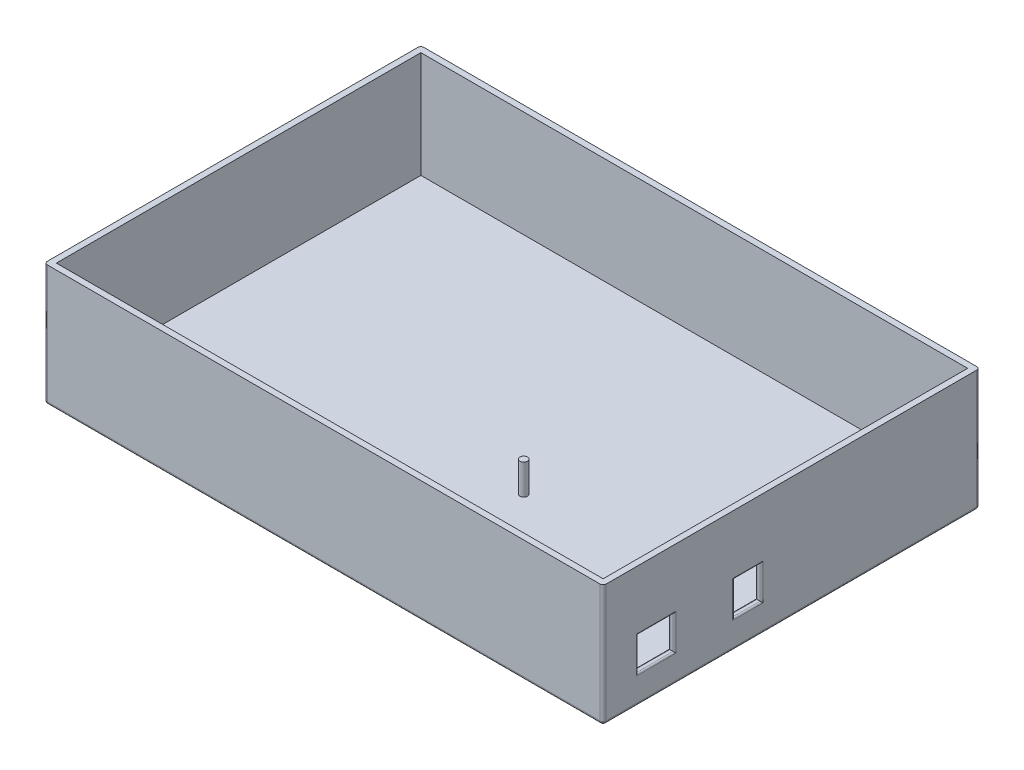
SolidWorks part; units mm, degrees
ref_plane "Ön Düzlem" through (0, 0, 0) normal (0, 0, 1) x (1, 0, 0)
ref_plane "Üst Düzlem" through (0, 0, 0) normal (0, 1, 0) x (1, 0, 0)
ref_plane "Sağ Düzlem" through (0, 0, 0) normal (1, 0, 0) x (0, 0, -1)
sketch "Çizim2" plane through (0, 0, 0) normal (0, 1, 0) x (1, 0, 0)
  line L1 (-92, -62) -> (92, -62)
  line L2 (-92, -62) -> (-92, 62)
  line L3 (-92, 62) -> (92, 62)
  line L4 (92, -62) -> (92, 62)
  line L5 (-92, -62) -> (92, 62) construction
  line L6 (-92, 62) -> (92, -62) construction
  circle A0 centre (17.8015, -42.9) radius 1.225
  circle A1 centre (17.8015, -14.95) radius 1.225
  circle A2 centre (68.6211, -58.05) radius 1.225
  circle A3 centre (69.9932, -9.75) radius 1.225
  point P0 (0, 0)
  dimension "D3" = 2.45
  dimension "D4" = 2.45
  dimension "D5" = 2.45
  dimension "D6" = 2.45
  dimension "D1" = 184
  dimension "D2" = 124
extrude "Yükseklik-Ekstrüzyon1" add sketch "Çizim2" along normal blind 40 contours L2 L1 L4 L3
sketch "Çizim3" plane through (0, 40, 0) normal (0, 1, 0) x (1, 0, 0)
  line L0 (-92, 62) -> (92, 62) construction
  line L1 (-90, -60) -> (90, -60)
  line L2 (-90, -60) -> (-90, 60)
  line L3 (-90, 60) -> (90, 60)
  line L4 (90, -60) -> (90, 60)
  line L5 (-90, -60) -> (90, 60) construction
  line L6 (-90, 60) -> (90, -60) construction
  point P0 (0, 0)
  dimension "D1" = 180
  dimension "D2" = 120
  dimension "D3" = 2
extrude "Kes-Ekstrüzyon1" cut sketch "Çizim3" against normal blind 35
sketch "Çizim4" plane through (0, 5, 0) normal (0, 1, 0) x (1, 0, 0)
  line L0 (90, -60) -> (90, -51.5) construction
  line L1 (90, -60) -> (90, 60) construction
  line L2 (90, -51.5) -> (90, -39.5)
  line L3 (90, -39.5) -> (102.829, -39.5)
  line L4 (102.829, -39.5) -> (102.829, -51.5)
  line L5 (102.829, -51.5) -> (90, -51.5)
  line L6 (90, -39.5) -> (90, -27.85) construction
  line L7 (90, -60) -> (90, 60) construction
  line L8 (90, -27.85) -> (90, -17.8423)
  line L9 (90, -17.8423) -> (115.4205, -17.8423)
  line L10 (115.4205, -17.8423) -> (115.4205, -26.8423)
  line L11 (115.4205, -26.8423) -> (90, -27.85)
  line L12 (90, -17.8423) -> (90, -27.85)
  dimension "D1" = 8.5
  dimension "D2" = 12
  dimension "D3" = 11.65
  dimension "D4" = 9
sketch "Çizim9" plane through (92, 0, 0) normal (1, 0, 0) x (0, 0, -1)
  line L0 (-45.5, 5) -> (-45.5, 9.3) construction
  line L1 (-51.5, 5) -> (-39.5, 5) construction
  line L3 (-50.5, 9.3) -> (-38.5, 9.3)
  line L4 (-38.5, 9.3) -> (-38.5, 20.3)
  line L5 (-38.5, 20.3) -> (-50.5, 20.3)
  line L6 (-50.5, 20.3) -> (-50.5, 9.3)
  line L7 (-18.85, 9.3) -> (-9.85, 9.3)
  line L8 (-9.85, 9.3) -> (-9.85, 20.3)
  line L9 (-9.85, 20.3) -> (-18.85, 20.3)
  line L10 (-18.85, 20.3) -> (-18.85, 9.3)
  line L11 (-62, 40) -> (-62, 0) construction
  dimension "D1" = 4.3
  dimension "D2" = 12
  dimension "D3" = 11
  dimension "D4" = 19.65
  dimension "D5" = 9
  dimension "D6" = 11.5
extrude "Kes-Ekstrüzyon3" cut sketch "Çizim9" against normal blind 57 and the other way blind 100
sketch "Çizim10" plane through (0, 5, 0) normal (0, 1, 0) x (1, 0, 0)
  line L0 (90, -60) -> (90, 60) construction
  line L1 (-90, 60) -> (-90, -60) construction
  line L4 (90, 60) -> (-90, 60) construction
  line L5 (-90, -60) -> (90, -60) construction
  line L6 (90, -60) -> (90, 60) construction
  circle A0 centre (70, -8.75) radius 1.225
  circle A1 centre (68.6, -57.05) radius 1.225
  circle A2 centre (17.84, -41.9) radius 1.225
  circle A3 centre (17.81, -13.95) radius 1.225
  dimension "D1" = 2.45
  dimension "D4" = 2.45
  dimension "D7" = 2.45
  dimension "D10" = 2.45
  dimension "D2" = 20
  dimension "D3" = 68.75
  dimension "D5" = 2.95
  dimension "D6" = 21.4
  dimension "D8" = 18.1
  dimension "D9" = 72.16
  dimension "D11" = 72.19
  dimension "D12" = 107.81
  dimension "D13" = 73.95
extrude "Yükseklik-Ekstrüzyon2" add sketch "Çizim10" along normal blind 10
fillet "Radyus1" radius 1 8 edges at (92, 0, 0) (0, 0, 62) (0, 0, -62) (-92, 0, 0) (92, 20, 62) (-92, 20, 62) (-92, 20, -62) (92, 20, -62)
fillet "Radyus2" radius 0.5 16 edges at (92, 14.8, 9.85) (90, 14.8, 9.85) (90, 20.3, 14.35) (92, 20.3, 14.35) (90, 14.8, 18.85) (92, 14.8, 18.85) (92, 9.3, 14.35) (90, 9.3, 14.35) (90, 14.8, 50.5) (90, 20.3, 44.5) (90, 14.8, 38.5) (90, 9.3, 44.5) (92, 14.8, 50.5) (92, 20.3, 44.5) (92, 14.8, 38.5) (92, 9.3, 44.5)
